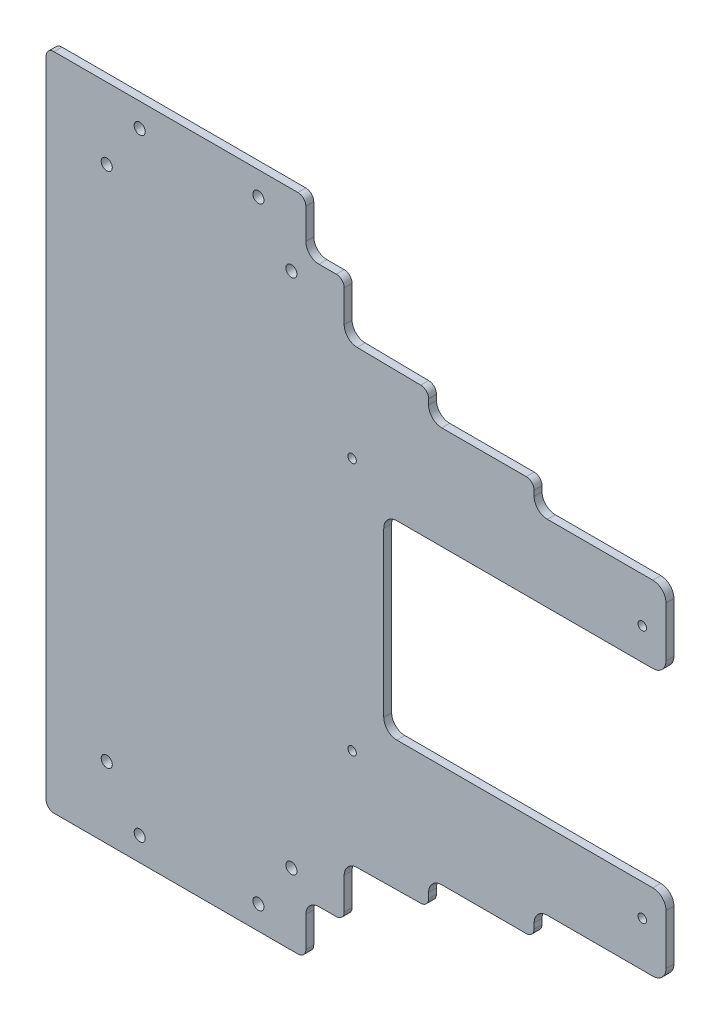
SolidWorks part; units mm, degrees
material "Thornel Mat VMA"
ref_plane "前视基准面" through (0, 0, 0) normal (0, 0, 1) x (1, 0, 0)
ref_plane "上视基准面" through (0, 0, 0) normal (0, 1, 0) x (1, 0, 0)
ref_plane "右视基准面" through (0, 0, 0) normal (1, 0, 0) x (0, 0, -1)
sketch "草图1" plane through (0, 0, 0) normal (0, 0, 1) x (1, 0, 0)
  line L1 (-117.5, -125) -> (117.5, -125)
  line L2 (-117.5, -125) -> (-117.5, 125)
  line L3 (-117.5, 125) -> (117.5, 125)
  line L4 (117.5, -125) -> (117.5, 125)
  line L5 (-117.5, -125) -> (117.5, 125) construction
  line L6 (-117.5, 125) -> (117.5, -125) construction
  point P0 (0, 0)
  dimension "D1" = 235
  dimension "D2" = 250
extrude "凸台-拉伸1" add sketch "草图1" along normal blind 3
sketch "草图2" plane through (0, 0, 3) normal (0, 0, 1) x (1, 0, 0)
  line L1 (117.5, 36) -> (10.5, 36)
  line L2 (117.5, 36) -> (117.5, -36)
  line L3 (117.5, -36) -> (10.5, -36)
  line L4 (10.5, 36) -> (10.5, -36)
  line L5 (117.5, 36) -> (10.5, -36) construction
  line L6 (117.5, -36) -> (10.5, 36) construction
  line L7 (117.5, -125) -> (117.5, 125) construction
  point P0 (64, 0)
  point P5 (0, 0)
  point P7 (0, 0)
  point P8 (74.9133, -9.1988)
  point P11 (0, 0)
  dimension "D1" = 72
  dimension "D2" = 107
extrude "切除-拉伸1" cut sketch "草图2" against normal through all
sketch "草图3" plane through (0, 0, 3) normal (0, 0, 1) x (1, 0, 0)
  line L0 (117.5, 125) -> (-117.5, 125) construction
  line L1 (-117.5, 125) -> (-117.5, -125) construction
  circle A0 centre (-94.5, 98) radius 2.1
  circle A1 centre (-24.5, 98) radius 2.1
  point P4 (0, 0)
  point P9 (0, 0)
  dimension "D1" = 4.2
  dimension "D2" = 70
  dimension "D3" = 27
  dimension "D4" = 23
extrude "切除-拉伸2" cut sketch "草图3" against normal blind 10
mirror "镜向1" about plane through (0, 0, 0) normal (0, 1, 0) of "切除-拉伸2"
sketch "草图4" plane through (0, 0, 3) normal (0, 0, 1) x (1, 0, 0)
  line L0 (117.5, 36) -> (117.5, 125) construction
  line L1 (117.5, 36) -> (10.5, 36) construction
  circle A0 centre (108.5, 48) radius 1.6
  circle A1 centre (-1.5, 48) radius 1.6
  circle A2 centre (108.5, -48) radius 1.6
  circle A3 centre (-1.5, -48) radius 1.6
  dimension "D1" = 3.2
  dimension "D2" = 9
  dimension "D3" = 12
  dimension "D4" = 2
  dimension "D5" = 2
extrude "切除-拉伸3" cut sketch "草图4" against normal blind 3
sketch "草图5" plane through (0, 0, 3) normal (0, 0, 1) x (1, 0, 0)
  line L0 (117.5, 125) -> (-117.5, 125) construction
  line L1 (117.5, 125) -> (27.5, 125)
  line L2 (117.5, 36) -> (117.5, 125) construction
  line L3 (117.5, 65) -> (117.5, 125)
  line L4 (67.5, 65) -> (67.5, 75)
  line L5 (67.5, 75) -> (27.5, 75)
  line L6 (27.5, 75) -> (27.5, 85)
  line L7 (67.5, 65) -> (117.5, 65)
  line L8 (-4.4966, 105.4469) -> (-4.4969, 85.4469)
  line L9 (117.5, 125) -> (-117.5, 125) construction
  line L10 (67.5, 75) -> (-117.5, 75) construction
  line L11 (67.5, 36) -> (67.5, 75) construction
  line L12 (117.5, 36) -> (117.5, 125) construction
  line L13 (-4.4969, 85.4469) -> (27.5, 85)
  line L14 (-4.0259, 125) -> (27.5, 125)
  line L15 (-19.0259, 125) -> (-19.0259, 105.4469)
  line L16 (-19.0259, 105.4469) -> (-4.4966, 105.4469)
  line L17 (-4.0259, 125) -> (-19.0259, 125)
  dimension "D2" = 90
  dimension "D3" = 60
  dimension "D4" = 32
  dimension "D5" = 10
  dimension "D6" = 15
  dimension "D7" = 20
  dimension "D1" = 50
extrude "切除-拉伸4" cut sketch "草图5" against normal through all
mirror "镜向2" about plane through (0, 0, 0) normal (0, 1, 0) of "切除-拉伸4"
sketch "草图6" plane through (0, 0, 3) normal (0, 0, 1) x (1, 0, 0)
  line L0 (-82, -116) -> (-37, -116) construction
  line L1 (-117.5, -125) -> (-19.0259, -125) construction
  line L2 (-117.5, 125) -> (-117.5, -125) construction
  circle A0 centre (-82, -116) radius 2.1
  circle A1 centre (-37, -116) radius 2.1
  point P6 (0, 0)
  dimension "D3" = 4.2
  dimension "D1" = 45
  dimension "D2" = 9
  dimension "D4" = 35.5
extrude "切除-拉伸5" cut sketch "草图6" against normal blind 3
mirror "镜向3" about plane through (0, 0, 0) normal (0, 1, 0) of "切除-拉伸5"
fillet "圆角1" radius 5 14 edges at (10.5, -36, 1.5) (10.5, 36, 1.5) (-4.4969, -85.4469, 1.5) (27.5, -75, 1.5) (67.5, -65, 1.5) (67.5, 65, 1.5) (27.5, 75, 1.5) (-4.4969, 85.4469, 1.5) (117.5, -65, 1.5) (117.5, -36, 1.5) (117.5, 36, 1.5) (117.5, 65, 1.5) (-19.0259, 105.4469, 1.5) (-19.0259, -105.4469, 1.5)
fillet "圆角2" radius 3 10 edges at (-117.5, 125, 1.5) (67.5, 75, 1.5) (27.5, 85, 1.5) (-117.5, -125, 1.5) (27.5, -85, 1.5) (67.5, -75, 1.5) (-19.0259, -125, 1.5) (-4.4966, -105.4469, 1.5) (-19.0259, 125, 1.5) (-4.4966, 105.4469, 1.5)
